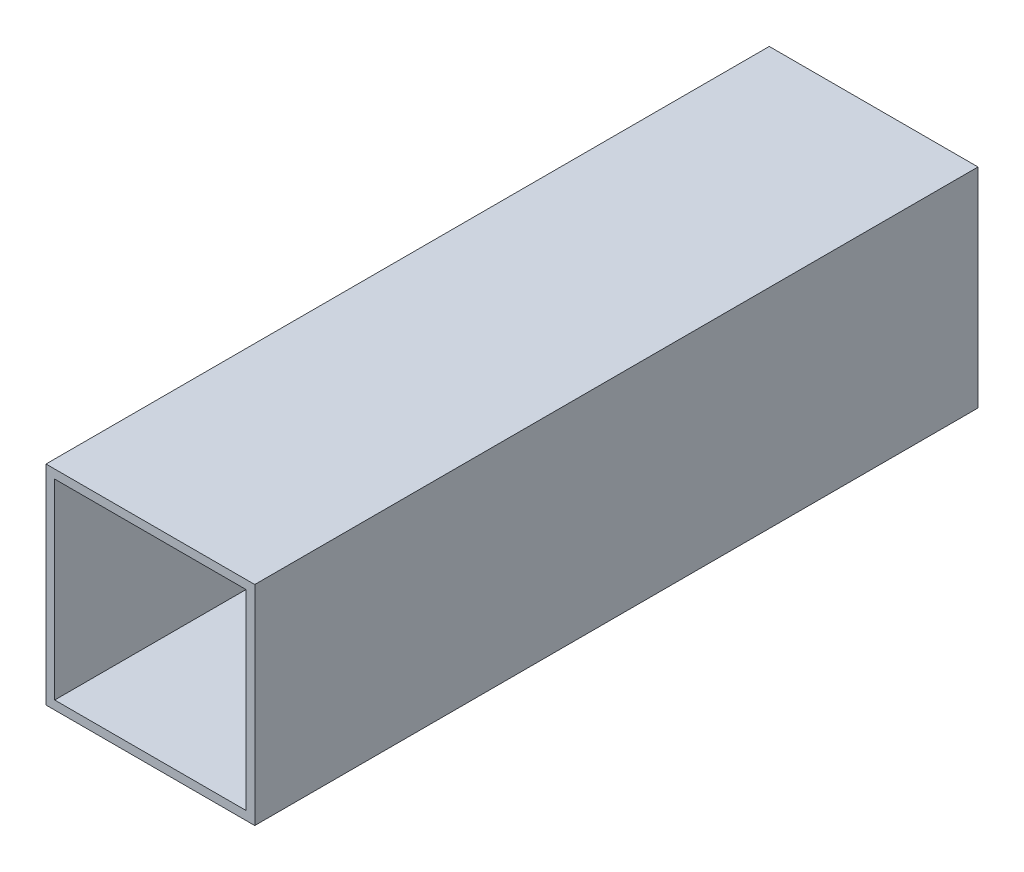
SolidWorks part; units mm, degrees
ref_plane "Front Plane" through (0, 0, 0) normal (0, 0, 1) x (1, 0, 0)
ref_plane "Top Plane" through (0, 0, 0) normal (0, 1, 0) x (1, 0, 0)
ref_plane "Right Plane" through (0, 0, 0) normal (1, 0, 0) x (0, 0, -1)
sketch "Sketch1" plane through (0, 0, 0) normal (0, 0, 1) x (1, 0, 0)
  line L0 (34.925, 34.925) -> (-34.925, 34.925)
  line L1 (38.1, -38.1) -> (-38.1, -38.1)
  line L2 (38.1, -38.1) -> (38.1, 38.1)
  line L3 (38.1, 38.1) -> (-38.1, 38.1)
  line L4 (-38.1, -38.1) -> (-38.1, 38.1)
  line L5 (38.1, -38.1) -> (-38.1, 38.1) construction
  line L6 (38.1, 38.1) -> (-38.1, -38.1) construction
  line L7 (-34.925, -34.925) -> (-34.925, 34.925)
  line L8 (34.925, -34.925) -> (-34.925, -34.925)
  line L9 (34.925, -34.925) -> (34.925, 34.925)
  point P0 (0, 0)
  dimension "D1" = 76.2
  dimension "D2" = 3.175
extrude "Boss-Extrude1" add sketch "Sketch1" along normal mid plane 264 contours L8 L9 L0 L7 | L3 L4 L1 L2
